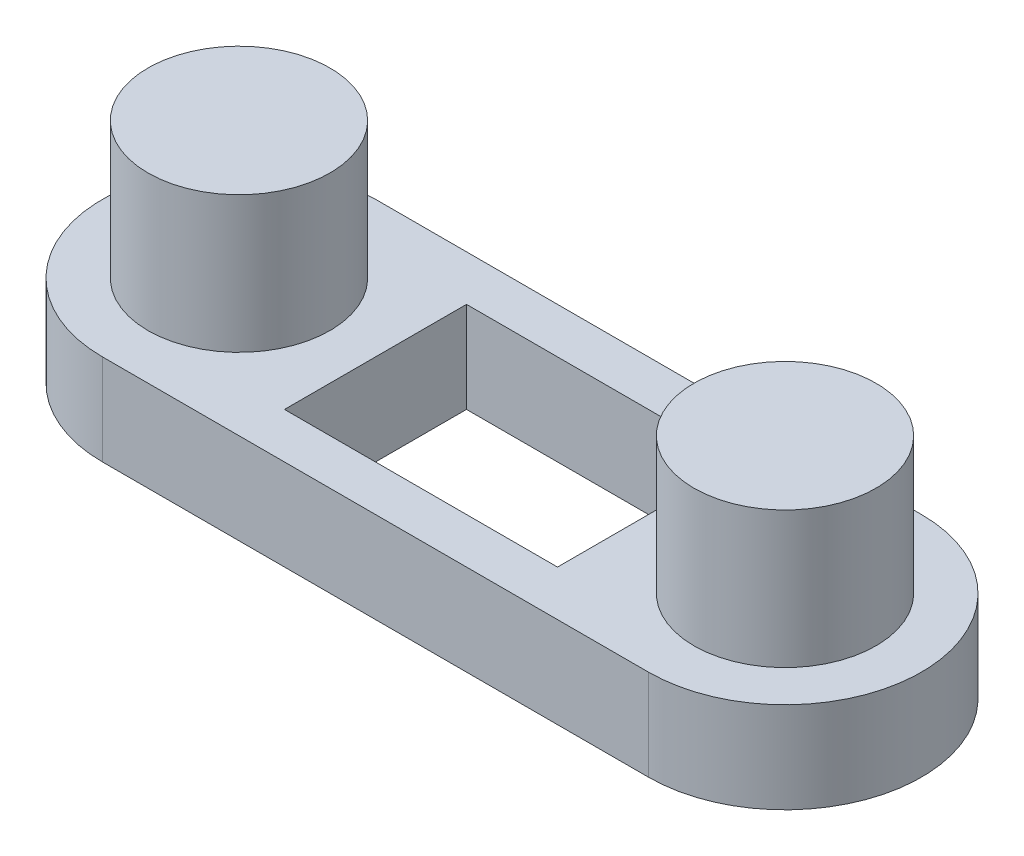
SolidWorks part; units mm, degrees
ref_plane "Front Plane" through (0, 0, 0) normal (0, 0, 1) x (1, 0, 0)
ref_plane "Top Plane" through (0, 0, 0) normal (0, 1, 0) x (1, 0, 0)
ref_plane "Right Plane" through (0, 0, 0) normal (1, 0, 0) x (0, 0, -1)
sketch "Sketch1" plane through (0, 0, 0) normal (0, 1, 0) x (1, 0, 0)
  line L0 (30, 15) -> (30, -15) construction
  line L1 (30, -15) -> (-30, -15)
  line L3 (30, 15) -> (-30, 15)
  line L5 (30, -15) -> (-30, 15) construction
  line L6 (30, 15) -> (-30, -15) construction
  line L7 (-30, 15) -> (-30, -15) construction
  arc A0 (-30, 15) -> (-30, -15) centre (-30, 0) ccw
  arc A1 (30, -15) -> (30, 15) centre (30, 0) ccw
  point P0 (0, 0)
  dimension "BaseLength" = 60
  dimension "BaseWidth" = 30
extrude "Boss-Extrude1" add sketch "Sketch1" along normal blind 10
sketch "Sketch2" plane through (0, 10, 0) normal (0, 1, 0) x (1, 0, 0)
  line L1 (15, -10) -> (-15, -10)
  line L2 (15, -10) -> (15, 10)
  line L3 (15, 10) -> (-15, 10)
  line L4 (-15, -10) -> (-15, 10)
  line L5 (15, -10) -> (-15, 10) construction
  line L6 (15, 10) -> (-15, -10) construction
  point P0 (0, 0)
  dimension "Cutlength" = 30
  dimension "D2" = 20
extrude "Cut-Extrude1" cut sketch "Sketch2" against normal blind 10
sketch "Sketch3" plane through (0, 10, 0) normal (0, 1, 0) x (1, 0, 0)
  circle A2 centre (-30, 0) radius 10
  circle A3 centre (30, 0) radius 10
  dimension "D1" = 20
  dimension "D2" = 20
extrude "Boss-Extrude2" add sketch "Sketch3" along normal blind 15 contours A2
sketch "Sketch4" plane through (0, 25, 0) normal (0, 1, 0) x (1, 0, 0)
  circle A0 centre (-30, 0) radius 5
  circle A1 centre (30, 0) radius 5
  dimension "D1" = 10
  dimension "D2" = 10
extrude "Cut-Extrude2" [suppressed] cut sketch "Sketch4" against normal through all
equation "\"A\"= 20"
equation "\"B\"= 10"
